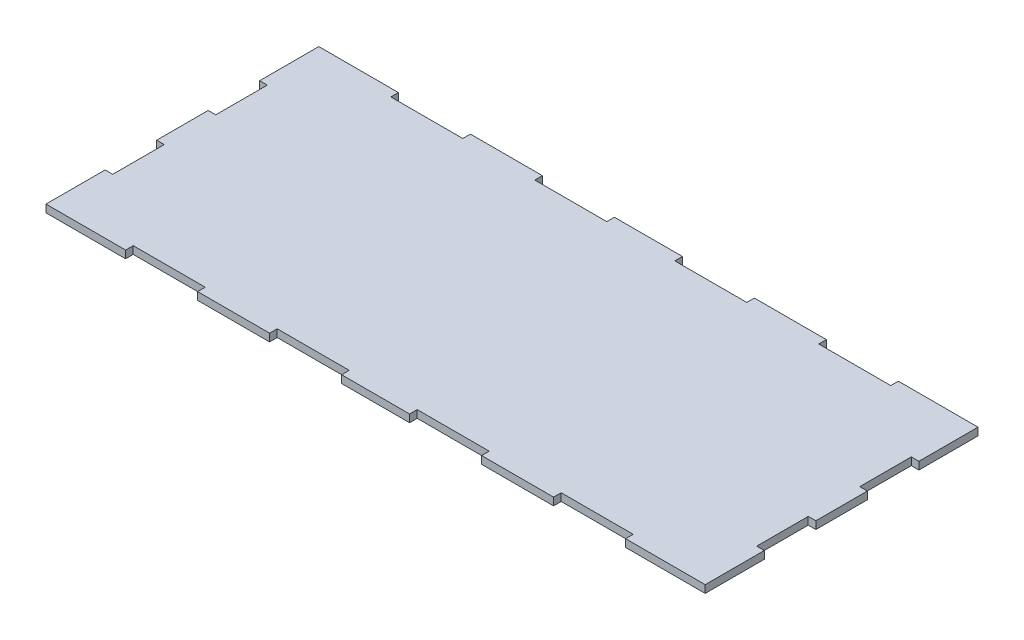
SolidWorks part; units mm, degrees
ref_plane "Front" through (0, 0, 0) normal (0, 0, 1) x (1, 0, 0)
ref_plane "Top" through (0, 0, 0) normal (0, 1, 0) x (1, 0, 0)
ref_plane "Right" through (0, 0, 0) normal (1, 0, 0) x (0, 0, -1)
sketch "Croquis1" plane through (0, 0, 0) normal (0, 1, 0) x (1, 0, 0)
  line L0 (0, 0) -> (0, 107.6) construction
  line L1 (3, 107.6) -> (31.4, 107.6)
  line L3 (260, 0) -> (0, 0) construction
  line L4 (0, 0) -> (0, 3)
  line L5 (0, 3) -> (0, 23.32)
  line L6 (0, 23.32) -> (3, 23.32)
  line L7 (3, 23.32) -> (3, 43.64)
  line L8 (0, 53.8) -> (260, 53.8) construction
  line L9 (3, 43.64) -> (0, 43.64)
  line L10 (3, 63.96) -> (0, 63.96)
  line L11 (3, 84.28) -> (3, 63.96)
  line L12 (0, 84.28) -> (3, 84.28)
  line L13 (0, 104.6) -> (0, 84.28)
  line L14 (0, 107.6) -> (0, 104.6)
  line L15 (0, 43.64) -> (0, 63.96)
  line L16 (130, 107.6) -> (130, 0) construction
  line L17 (260, 0) -> (260, 107.6) construction
  line L18 (260, 43.64) -> (260, 63.96)
  line L19 (31.4, 107.6) -> (31.4, 104.6)
  line L20 (260, 104.6) -> (260, 84.28)
  line L21 (260, 84.28) -> (257, 84.28)
  line L22 (257, 84.28) -> (257, 63.96)
  line L23 (257, 63.96) -> (260, 63.96)
  line L24 (257, 43.64) -> (260, 43.64)
  line L25 (257, 23.32) -> (257, 43.64)
  line L26 (260, 23.32) -> (257, 23.32)
  line L27 (260, 3) -> (260, 23.32)
  line L28 (260, 0) -> (260, 3)
  line L29 (31.4, 104.6) -> (59.8, 104.6)
  line L30 (59.8, 104.6) -> (59.8, 107.6)
  line L31 (0, 107.6) -> (3, 107.6)
  line L32 (59.8, 107.6) -> (88.2, 107.6)
  line L33 (88.2, 107.6) -> (88.2, 104.6)
  line L34 (88.2, 104.6) -> (116.6, 104.6)
  line L35 (116.6, 104.6) -> (116.6, 107.6)
  line L36 (143.4, 104.6) -> (143.4, 107.6)
  line L37 (171.8, 104.6) -> (143.4, 104.6)
  line L38 (171.8, 107.6) -> (171.8, 104.6)
  line L39 (200.2, 107.6) -> (171.8, 107.6)
  line L40 (200.2, 104.6) -> (200.2, 107.6)
  line L41 (228.6, 104.6) -> (200.2, 104.6)
  line L42 (228.6, 107.6) -> (228.6, 104.6)
  line L43 (257, 107.6) -> (228.6, 107.6)
  line L44 (116.6, 107.6) -> (143.4, 107.6)
  line L45 (260, 0) -> (257, 0)
  line L46 (260, 107.6) -> (257, 107.6)
  line L47 (0, 0) -> (3, 0)
  line L48 (260, 107.6) -> (260, 104.6)
  line L49 (3, 0) -> (31.4, 0)
  line L50 (116.6, 0) -> (143.4, 0)
  line L51 (257, 0) -> (228.6, 0)
  line L52 (228.6, 0) -> (228.6, 3)
  line L53 (228.6, 3) -> (200.2, 3)
  line L54 (200.2, 3) -> (200.2, 0)
  line L55 (200.2, 0) -> (171.8, 0)
  line L56 (171.8, 0) -> (171.8, 3)
  line L57 (171.8, 3) -> (143.4, 3)
  line L58 (143.4, 3) -> (143.4, 0)
  line L59 (116.6, 3) -> (116.6, 0)
  line L60 (88.2, 3) -> (116.6, 3)
  line L61 (88.2, 0) -> (88.2, 3)
  line L62 (59.8, 0) -> (88.2, 0)
  line L63 (59.8, 3) -> (59.8, 0)
  line L64 (31.4, 3) -> (59.8, 3)
  line L65 (31.4, 0) -> (31.4, 3)
  dimension "D1" = 107.6
  dimension "D2" = 260
  dimension "D3" = 3
  dimension "D4" = 20.32
  dimension "D6" = 28.4
  dimension "D7" = 3
extrude "Saliente-Extruir1" add sketch "Croquis1" along normal blind 3
